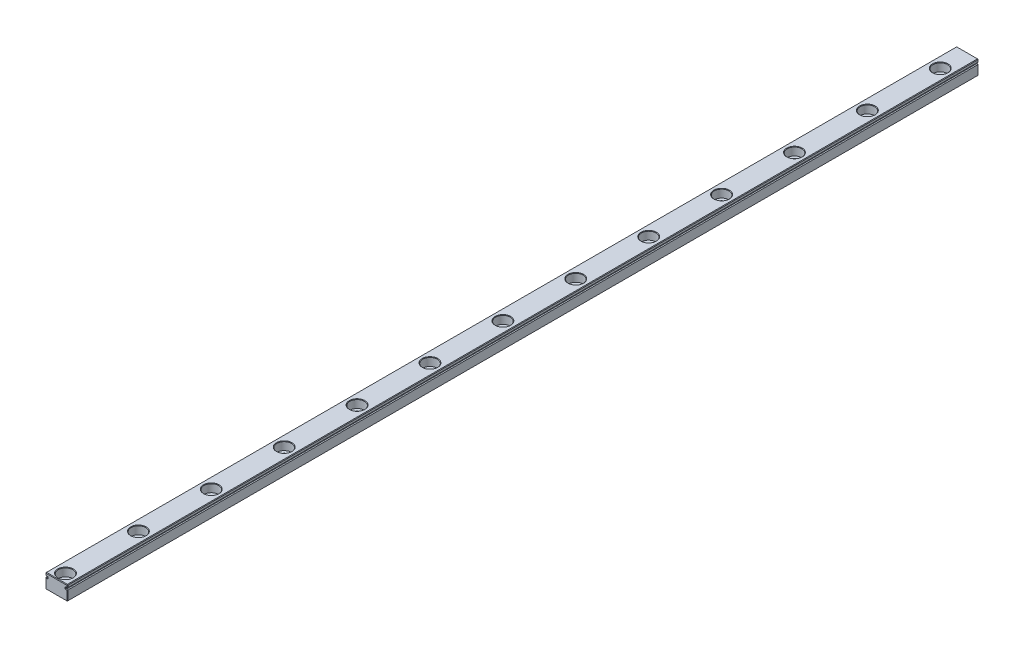
SolidWorks part; units mm, degrees
material "AISI 304"
ref_plane "Front Plane" through (0, 0, 0) normal (0, 0, 1) x (1, 0, 0)
ref_plane "Top Plane" through (0, 0, 0) normal (0, 1, 0) x (1, 0, 0)
ref_plane "Right Plane" through (0, 0, 0) normal (1, 0, 0) x (0, 0, -1)
sketch "Sketch1" plane through (0, 0, 0) normal (0, 0, 1) x (1, 0, 0)
  line L0 (0, 0) -> (0, 8) construction
  line L1 (0, 8) -> (12, 8)
  line L2 (0, 0) -> (12, 0)
  line L3 (0, 8) -> (0, 6.75)
  line L4 (0, 6.75) -> (0.5, 6.25) construction
  line L5 (0.5, 6.25) -> (1, 6.25)
  line L6 (0.5, 5.75) -> (0, 5.25) construction
  line L7 (0, 5.25) -> (0, 0)
  line L8 (1, 6.25) -> (1, 5.75)
  line L9 (1, 5.75) -> (0.5, 5.75)
  line L10 (0.5, 5.75) -> (0.75, 6) construction
  line L11 (0.75, 6) -> (0.5, 6.25) construction
  line L12 (0, 6.75) -> (0, 6.559)
  line L13 (0, 5.25) -> (0, 5.441)
  line L14 (6, 8) -> (6, 0) construction
  line L15 (11.25, 6) -> (11.5, 6.25) construction
  line L16 (11.5, 5.75) -> (11.25, 6) construction
  line L17 (11.5, 5.75) -> (12, 5.25) construction
  line L18 (12, 6.75) -> (11.5, 6.25) construction
  line L19 (12, 0) -> (12, 8) construction
  line L20 (12, 5.25) -> (12, 5.441)
  line L21 (12, 6.75) -> (12, 6.559)
  line L22 (11, 5.75) -> (11.5, 5.75)
  line L23 (11, 6.25) -> (11, 5.75)
  line L24 (12, 5.25) -> (12, 0)
  line L25 (11.5, 6.25) -> (11, 6.25)
  line L26 (12, 8) -> (12, 6.75)
  arc A0 (0, 5.441) -> (0.5, 5.75) centre (0, 6) ccw
  arc A1 (0.5, 6.25) -> (0, 6.559) centre (0, 6) ccw
  arc A2 (11.5, 6.25) -> (12, 6.559) centre (12, 6) cw
  arc A3 (12, 5.441) -> (11.5, 5.75) centre (12, 6) cw
  point P4 (1, 6)
  point P28 (11, 6)
  dimension "D1" = 8
  dimension "D2" = 6
  dimension "D3" = 0.5
  dimension "D4" = 45
  dimension "D5" = 2
  dimension "D6" = 1
extrude "Boss-Extrude1" add sketch "Sketch1" along normal blind 500
chamfer "Chamfer1" distance 0.3 angle 45 36 edges at (0, 0, 250) (12, 0, 250) (0, 8, 250) (12, 8, 250) (0.2939, 5.5245, 500) (0.75, 5.75, 500) (1, 6, 500) (0.75, 6.25, 500) (0.2939, 6.4755, 500) (0, 7.2795, 500) (6, 8, 500) (12, 7.2795, 500) (11.7061, 6.4755, 500) (11.25, 6.25, 500) (11, 6, 500) (11.25, 5.75, 500) (11.7061, 5.5245, 500) (12, 2.7205, 500) (6, 0, 500) (0, 2.7205, 500) (12, 2.7205, 0) (11.7061, 5.5245, 0) (11.25, 5.75, 0) (11, 6, 0) (11.25, 6.25, 0) (11.7061, 6.4755, 0) (12, 7.2795, 0) (6, 0, 0) (0, 2.7205, 0) (0.2939, 5.5245, 0) (0.75, 5.75, 0) (1, 6, 0) (0.75, 6.25, 0) (0.2939, 6.4755, 0) (0, 7.2795, 0) (6, 8, 0)
hole_wizard "CBORE for M5 Hex Head Bolt1" positions "3DSketch1" profile "Sketch3" counterbore size "M5" standard "ANSI Metric" end condition through all
sketch3d "3DSketch1"
  line L0 (6, 8, 0) -> (6, 8, 15) construction
  line L1 (11.7, 8, 0) -> (0.3, 8, 0) construction
  point P0 (6, 8, 15)
  dimension "D1" = 15
sketch "Sketch3" plane through (6, 8, 15) normal (1, 0, 0) x (0, 0, 1)
  line L0 (0, 0) -> (0, 8)
  line L1 (2.25, 7.75) -> (2.5, 8)
  line L2 (4, 4.5) -> (2.25, 4.5)
  line L3 (2.25, 4.5) -> (2.25, 7.75)
  line L5 (4, 4.5) -> (4, 0.25)
  line L6 (4, 0.25) -> (4.25, 0)
  line L7 (4.25, 0) -> (0, 0)
  line L8 (-4, 0.25) -> (-4.25, 0) construction
  line L11 (0, -6.35) -> (0, 107.95) construction
  line L12 (2.5, 8) -> (0, 8)
  line L13 (-2.25, 7.75) -> (-2.5, 8) construction
  dimension "Thru Hole Dia." = 4.5
  dimension "Thru Hole Depth" = 8
  dimension "C'Bore Dia." = 8
  dimension "C'Bore Depth" = 4.5
  dimension "Near C'Sink Dia." = 8.5
  dimension "Near C'Sink Angle" = 90
  dimension "Far C'Sink Dia." = 5
  dimension "Far C'Sink Angle" = 90
pattern_linear "LPattern1" count 13 spacing 40 along (0, 0, 1) of "CBORE for M5 Hex Head Bolt1"
